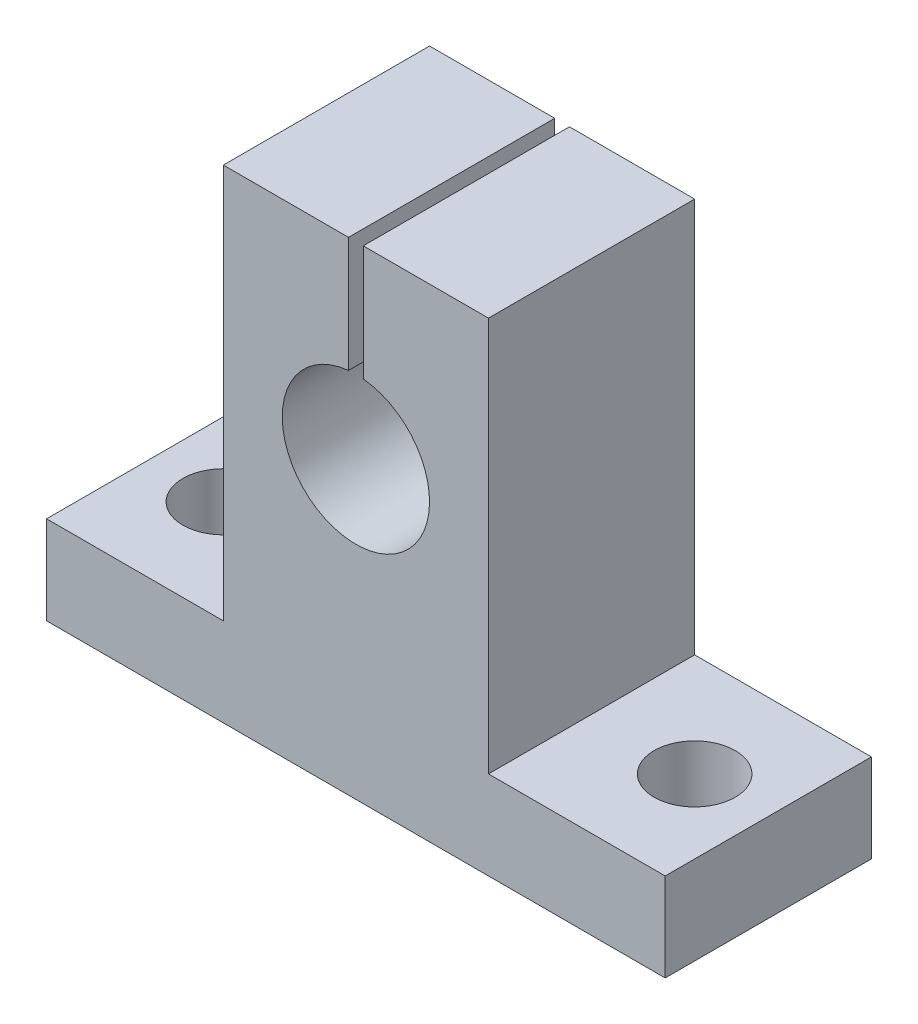
SolidWorks part; units mm, degrees
ref_plane "Front Plane" through (0, 0, 0) normal (0, 0, 1) x (1, 0, 0)
ref_plane "Top Plane" through (0, 0, 0) normal (0, 1, 0) x (1, 0, 0)
ref_plane "Right Plane" through (0, 0, 0) normal (1, 0, 0) x (0, 0, -1)
sketch "Sketch1" plane through (0, 0, 0) normal (0, 0, 1) x (1, 0, 0)
  line L0 (0, 12.8) -> (0, -20) construction
  line L1 (9, 12.8) -> (-9, 12.8)
  line L2 (-9, 12.8) -> (-9, -14)
  line L3 (-9, -14) -> (-21, -14)
  line L4 (-21, -14) -> (-21, -20)
  line L5 (-21, -20) -> (21, -20)
  line L6 (21, -14) -> (21, -20)
  line L7 (9, -14) -> (21, -14)
  line L8 (9, 12.8) -> (9, -14)
  circle A0 centre (0, 0) radius 5
  dimension "D1" = 10
  dimension "D2" = 18
  dimension "D3" = 42
  dimension "D4" = 32.8
  dimension "D5" = 20
  dimension "D6" = 6
extrude "Boss-Extrude1" add sketch "Sketch1" along normal blind 14
sketch "Sketch2" plane through (0, 0, 14) normal (0, 0, 1) x (1, 0, 0)
  line L2 (0.5, -0.6708) -> (-0.5, -0.6708)
  line L3 (0.5, -0.6708) -> (0.5, 14.6769)
  line L4 (0.5, 14.6769) -> (-0.5, 14.6769)
  line L5 (-0.5, -0.6708) -> (-0.5, 14.6769)
  line L6 (0.5, -0.6708) -> (-0.5, 14.6769) construction
  line L7 (0.5, 14.6769) -> (-0.5, -0.6708) construction
  point P0 (0, 7.0031)
extrude "Cut-Extrude1" cut sketch "Sketch2" against normal through all
sketch "Sketch3" plane through (0, -14, 0) normal (0, 1, 0) x (1, 0, 0)
  line L0 (0, 0) -> (0, -14) construction
  line L1 (-5, -14) -> (5, -14) construction
  circle A0 centre (-16, -7) radius 2.75
  circle A1 centre (16, -7) radius 2.75
  point P9 (0, -7)
  dimension "D1" = 5.5
  dimension "D2" = 32
extrude "Cut-Extrude2" cut sketch "Sketch3" against normal through all
